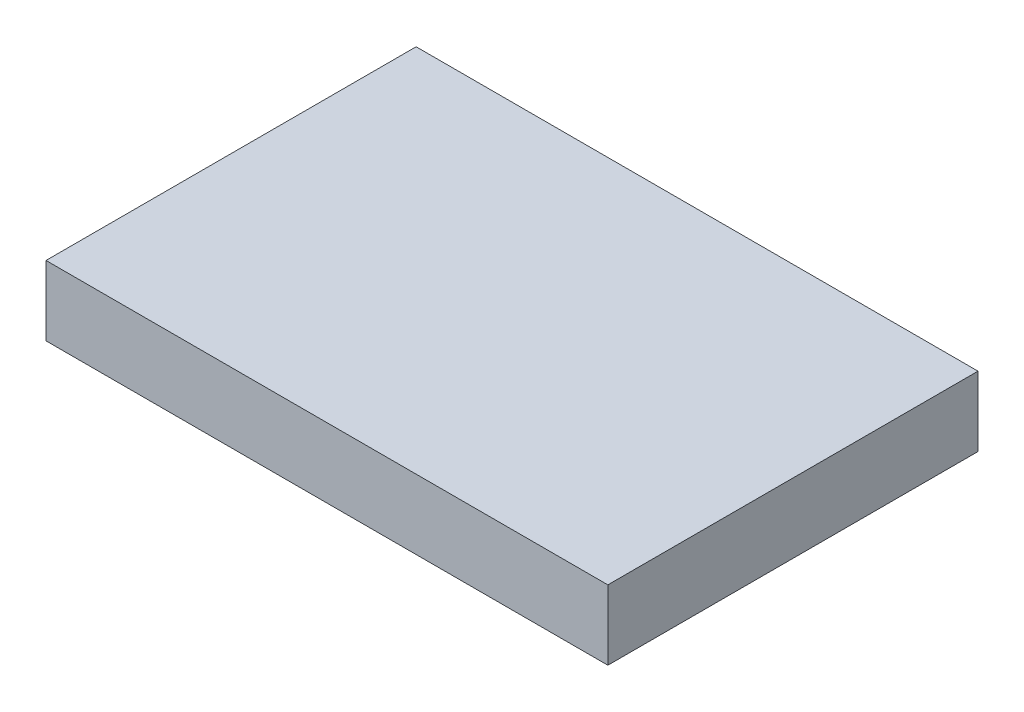
SolidWorks part; units mm, degrees
ref_plane "Front Plane" through (0, 0, 0) normal (0, 0, 1) x (1, 0, 0)
ref_plane "Top Plane" through (0, 0, 0) normal (0, 1, 0) x (1, 0, 0)
ref_plane "Right Plane" through (0, 0, 0) normal (1, 0, 0) x (0, 0, -1)
sketch "Sketch1" plane through (0, 0, 0) normal (0, 1, 0) x (1, 0, 0)
  line L1 (0, 0) -> (80.6939, 0)
  line L2 (0, 0) -> (0, 53.1574)
  line L3 (0, 53.1574) -> (80.6939, 53.1574)
  line L4 (80.6939, 0) -> (80.6939, 53.1574)
extrude "Boss-Extrude1" add sketch "Sketch1" along normal blind 10
